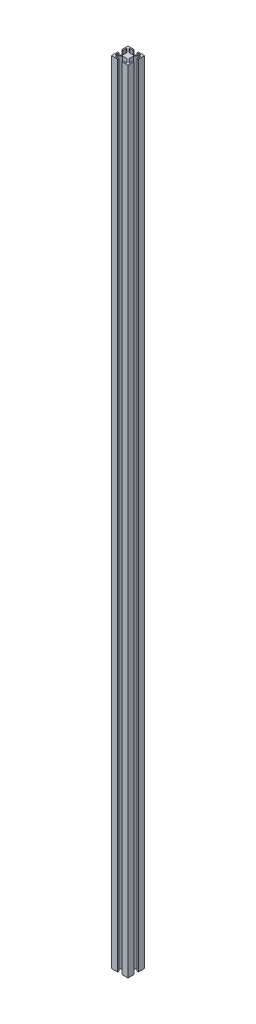
SolidWorks part; units mm, degrees
ref_plane "Plan de face" through (0, 0, 0) normal (0, 0, 1) x (1, 0, 0)
ref_plane "Plan de dessus" through (0, 0, 0) normal (0, 1, 0) x (1, 0, 0)
ref_plane "Plan de droite" through (0, 0, 0) normal (1, 0, 0) x (0, 0, -1)
sketch "Esquisse1" plane through (0, 0, 0) normal (0, 1, 0) x (1, 0, 0)
  line L0 (6.1245, 16.1036) -> (30.6226, 16.1036) construction
  line L6 (-11.5924, 0) -> (12.1076, 0) construction
  line L7 (0, 12.3466) -> (0, -12.7449) construction
  line L12 (-10, -10) -> (10, 10) construction
  line L59 (-10, -2.5) -> (-10, -10)
  line L60 (-10, -2.5) -> (-8.5, -2.5)
  line L69 (-8.5, -2.5) -> (-8.5, -6.2322)
  line L70 (-7.6464, -6.5858) -> (-3.75, -2.6893)
  line L73 (-6.5858, -7.6464) -> (-2.6893, -3.75)
  line L74 (-2.5, -8.5) -> (-6.2322, -8.5)
  line L75 (-2.5, -10) -> (-2.5, -8.5)
  line L76 (-2.5, -10) -> (-10, -10)
  line L77 (-2.5, 10) -> (-2.5, 8.5)
  line L78 (-2.5, 10) -> (-10, 10)
  line L79 (-10, 2.5) -> (-10, 10)
  line L80 (-10, 2.5) -> (-8.5, 2.5)
  line L81 (-8.5, 2.5) -> (-8.5, 6.2322)
  line L82 (-7.6464, 6.5858) -> (-3.75, 2.6893)
  line L83 (-6.5858, 7.6464) -> (-2.6893, 3.75)
  line L84 (-2.5, 8.5) -> (-6.2322, 8.5)
  line L85 (10, 2.5) -> (8.5, 2.5)
  line L86 (10, 2.5) -> (10, 10)
  line L87 (2.5, 10) -> (10, 10)
  line L88 (2.5, 10) -> (2.5, 8.5)
  line L89 (2.5, 8.5) -> (6.2322, 8.5)
  line L90 (6.5858, 7.6464) -> (2.6893, 3.75)
  line L91 (7.6464, 6.5858) -> (3.75, 2.6893)
  line L92 (8.5, 2.5) -> (8.5, 6.2322)
  line L93 (2.5, -10) -> (2.5, -8.5)
  line L94 (2.5, -10) -> (10, -10)
  line L95 (10, -2.5) -> (10, -10)
  line L96 (10, -2.5) -> (8.5, -2.5)
  line L97 (8.5, -2.5) -> (8.5, -6.2322)
  line L98 (7.6464, -6.5858) -> (3.75, -2.6893)
  line L99 (6.5858, -7.6464) -> (2.6893, -3.75)
  line L100 (2.5, -8.5) -> (6.2322, -8.5)
  line L101 (-3.75, 2.6893) -> (-3.75, -2.6893)
  line L102 (-2.6893, -3.75) -> (2.6893, -3.75)
  line L103 (-2.6893, 3.75) -> (2.6893, 3.75)
  line L104 (3.75, 2.6893) -> (3.75, -2.6893)
  arc A0 (-8.5, 6.2322) -> (-7.6464, 6.5858) centre (-8, 6.2322) cw
  arc A1 (-8.5, -6.2322) -> (-7.6464, -6.5858) centre (-8, -6.2322) ccw
  arc A2 (-6.5858, -7.6464) -> (-6.2322, -8.5) centre (-6.2322, -8) ccw
  arc A3 (6.5858, -7.6464) -> (6.2322, -8.5) centre (6.2322, -8) cw
  arc A4 (8.5, -6.2322) -> (7.6464, -6.5858) centre (8, -6.2322) cw
  arc A5 (7.6464, 6.5858) -> (8.5, 6.2322) centre (8, 6.2322) cw
  arc A6 (6.2322, 8.5) -> (6.5858, 7.6464) centre (6.2322, 8) cw
  arc A7 (-6.5858, 7.6464) -> (-6.2322, 8.5) centre (-6.2322, 8) cw
  point P7 (-2.5, -9.25)
  point P8 (2.5, -9.25)
  point P15 (-8.5, -7.4393)
  point P51 (0, 0)
  point P52 (-7.4393, -8.5)
  dimension "D2" = 5
  dimension "D7" = 0.5
  dimension "D1" = 20
  dimension "D3" = 4
  dimension "D4" = 7.5
  dimension "D5" = 1.5
  dimension "D6" = 1.5
extrude "Boss.-Extru.1" add sketch "Esquisse1" along normal blind 950
